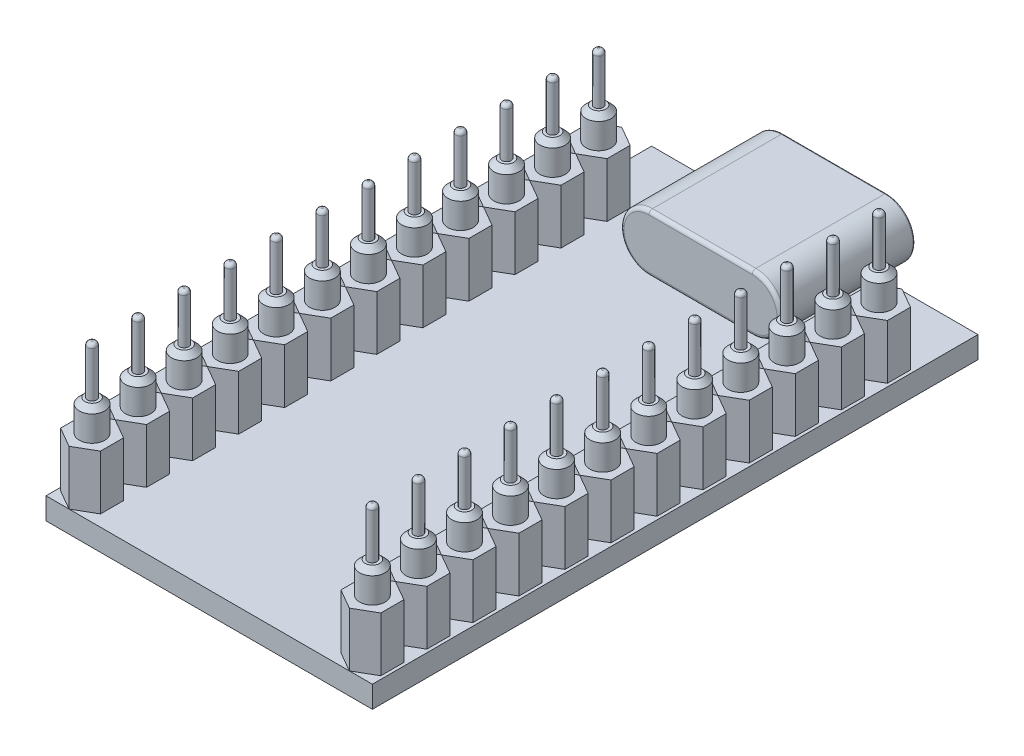
SolidWorks part; units mm, degrees
ref_plane "Front Plane" through (0, 0, 0) normal (0, 0, 1) x (1, 0, 0)
ref_plane "Top Plane" through (0, 0, 0) normal (0, 1, 0) x (1, 0, 0)
ref_plane "Right Plane" through (0, 0, 0) normal (1, 0, 0) x (0, 0, -1)
sketch "Sketch1" plane through (0, 0, 0) normal (0, 1, 0) x (1, 0, 0)
  line L1 (9, 16.7) -> (-9, 16.7)
  line L2 (9, 16.7) -> (9, -16.7)
  line L3 (9, -16.7) -> (-9, -16.7)
  line L4 (-9, 16.7) -> (-9, -16.7)
  line L5 (9, 16.7) -> (-9, -16.7) construction
  line L6 (9, -16.7) -> (-9, 16.7) construction
  point P0 (0, 0)
  dimension "D1" = 33.4
  dimension "D2" = 18
extrude "Boss-Extrude1" add sketch "Sketch1" along normal blind 1.2
sketch "Sketch2" plane through (0, 0, -16.7) normal (0, 0, -1) x (-1, 0, 0)
  line L0 (-2.85, 2.77) -> (2.85, 2.77) construction
  line L1 (-2.85, 4.34) -> (2.85, 4.34)
  line L2 (-2.85, 1.2) -> (2.85, 1.2)
  line L3 (-4.42, 2.77) -> (-4.42, 4.7132) construction
  line L4 (4.42, 2.77) -> (4.42, 4.7132) construction
  line L5 (-4.42, 4.7132) -> (4.42, 4.7132) construction
  line L8 (-9, 1.2) -> (9, 1.2) construction
  line L9 (0, 0) -> (0, 4.7132) construction
  arc A0 (-2.85, 4.34) -> (-2.85, 1.2) centre (-2.85, 2.77) ccw
  arc A1 (2.85, 1.2) -> (2.85, 4.34) centre (2.85, 2.77) ccw
  point P2 (0, 2.77)
  dimension "D1" = 8.84
  dimension "D4" = 3.14
extrude "Boss-Extrude2" add sketch "Sketch2" along normal blind 1.1 and the other way blind 6.3 separate body
sketch "Sketch3" plane through (0, 0, -17.8) normal (0, 0, -1) x (-1, 0, 0)
  line L2 (-2.85, 2.77) -> (2.85, 2.77) construction
  line L3 (-2.85, 3.02) -> (2.85, 3.02)
  line L4 (-2.85, 1.5) -> (2.85, 1.5)
  line L5 (2.85, 4.04) -> (-2.85, 4.04)
  line L6 (-2.85, 1.5) -> (2.85, 1.5)
  line L7 (2.85, 4.04) -> (-2.85, 4.04)
  line L8 (-2.85, 2.52) -> (2.85, 2.52)
  arc A2 (-2.85, 3.02) -> (-2.85, 2.52) centre (-2.85, 2.77) ccw
  arc A3 (2.85, 2.52) -> (2.85, 3.02) centre (2.85, 2.77) ccw
  arc A4 (-2.85, 4.04) -> (-2.85, 1.5) centre (-2.85, 2.77) ccw
  arc A5 (2.85, 1.5) -> (2.85, 4.04) centre (2.85, 2.77) ccw
  arc A6 (-2.85, 4.04) -> (-2.85, 1.5) centre (-2.85, 2.77) ccw
  arc A7 (2.85, 1.5) -> (2.85, 4.04) centre (2.85, 2.77) ccw
  point P0 (0, 2.77)
  dimension "D2" = 0.5
  dimension "D1" = 0.3
fillet "Fillet1" radius 0.1 4 edges at (0, 4.34, -17.8) (-4.42, 2.77, -17.8) (0, 1.2, -17.8) (4.42, 2.77, -17.8)
fillet "Fillet3" radius 0.2 4 edges at (-4.42, 2.77, -10.4) (0, 1.2, -10.4) (4.42, 2.77, -10.4) (0, 4.34, -10.4)
extrude "Cut-Extrude2" cut sketch "Sketch3" against normal blind 7
fillet "Fillet4" radius 0.1 8 edges at (0, 4.04, -17.8) (-4.12, 2.77, -17.8) (0, 1.5, -17.8) (-3.1, 2.77, -17.8) (0, 2.52, -17.8) (3.1, 2.77, -17.8) (0, 3.02, -17.8) (4.12, 2.77, -17.8)
sketch "Sketch4" plane through (0, 1.2, 0) normal (0, 1, 0) x (1, 0, 0)
  line L0 (-7.73, 16.7) -> (-7.73, -16.7) construction
  line L1 (9, 16.7) -> (-9, 16.7) construction
  line L2 (-9, -16.7) -> (9, -16.7) construction
  line L3 (-9, 16.7) -> (-9, -16.7) construction
  circle A0 centre (-7.73, -15.43) radius 0.5
  circle A1 centre (-7.73, -12.89) radius 0.5
  circle A2 centre (-7.73, -10.35) radius 0.5
  circle A3 centre (-7.73, -7.81) radius 0.5
  circle A4 centre (-7.73, -5.27) radius 0.5
  circle A5 centre (-7.73, -2.73) radius 0.5
  circle A6 centre (-7.73, -0.19) radius 0.5
  circle A7 centre (-7.73, 2.35) radius 0.5
  circle A8 centre (-7.73, 4.89) radius 0.5
  circle A9 centre (-7.73, 7.43) radius 0.5
  circle A10 centre (-7.73, 9.97) radius 0.5
  circle A11 centre (-7.73, 12.51) radius 0.5
  dimension "D2" = 1
  dimension "D1" = 1.27
  dimension "D3" = 1.27
  dimension "D5" = 2.54
  dimension "D4" = 12
extrude "Cut-Extrude3" cut sketch "Sketch4" against normal blind 7
ref_plane "Plane1" through (0, 0.6, 0) normal (0, -1, 0) x (-1, 0, 0)
sketch "Sketch7" plane through (0, 0.6, 0) normal (0, -1, 0) x (-1, 0, 0)
  circle A0 centre (7.73, -15.43) radius 1
  circle A1 centre (7.73, -12.89) radius 1
  circle A2 centre (7.73, -10.35) radius 1
  circle A3 centre (7.73, -7.81) radius 1
  circle A4 centre (7.73, -5.27) radius 1
  circle A5 centre (7.73, -2.73) radius 1
  circle A6 centre (7.73, -0.19) radius 1
  circle A7 centre (7.73, 2.35) radius 1
  circle A8 centre (7.73, 4.89) radius 1
  circle A9 centre (7.73, 7.43) radius 1
  circle A10 centre (7.73, 9.97) radius 1
  circle A11 centre (7.73, 12.51) radius 1
  dimension "D1" = 2
  dimension "D3" = 2.54
  dimension "D2" = 12
extrude "Cut-Extrude6" cut sketch "Sketch7" against normal blind 0.1 from surface at 0.6 starting at face at (-7.73, 0, 14.93)
sketch "Sketch9" plane through (0, 1.2, 0) normal (0, 1, 0) x (1, 0, 0)
  circle A0 centre (-7.73, -15.43) radius 0.25
  dimension "D1" = 0.5
extrude "Boss-Extrude3" add sketch "Sketch9" along normal blind 7.4 and the other way blind 1.6 separate body
fillet "Fillet5" radius 0.2 2 edges at (-7.73, -0.4, 15.68) (-7.73, 8.6, 15.68)
sketch "Sketch10" plane through (0, 1.2, 0) normal (0, 1, 0) x (1, 0, 0)
  line L0 (-9, 16.7) -> (-9, -16.7) construction
  line L1 (-8.8299, -14.795) -> (-8.8299, -16.065)
  line L2 (-8.8299, -16.065) -> (-7.73, -16.7)
  line L3 (-7.73, -16.7) -> (-6.6301, -16.065)
  line L4 (-6.6301, -16.065) -> (-6.6301, -14.795)
  line L5 (-6.6301, -14.795) -> (-7.73, -14.16)
  line L6 (-7.73, -14.16) -> (-8.8299, -14.795)
  line L7 (-9, -16.7) -> (9, -16.7) construction
  circle A0 centre (-7.73, -15.43) radius 1.0999 construction
extrude "Boss-Extrude4" add sketch "Sketch10" along normal blind 3 separate body
sketch "Sketch11" plane through (0, 1.2, 0) normal (0, 1, 0) x (1, 0, 0)
  circle A0 centre (-7.73, -15.43) radius 0.7
  dimension "D1" = 1.4
extrude "Boss-Extrude5" add sketch "Sketch11" along normal blind 4.7 separate body
chamfer "Chamfer1" distance 0.3 angle 45 1 edges at (-7.73, 5.9, 16.13)
pattern_linear "LPattern2" count 12 spacing 2.54 along (0, 0, -1) of bodies 110 112 111
mirror "Mirror2" about plane through (0, 0, 0) normal (1, 0, 0) of bodies 118 125 122 130 141 135 113 112 117 128 140 111 121 133 145 126 139 116 131 120 144 124 138 129 115 134 143 110 119 137 123 127 132 142 114 136
mirror "Mirror5" about plane through (0, 0, 0) normal (1, 0, 0) of "Cut-Extrude6", "Cut-Extrude3"
